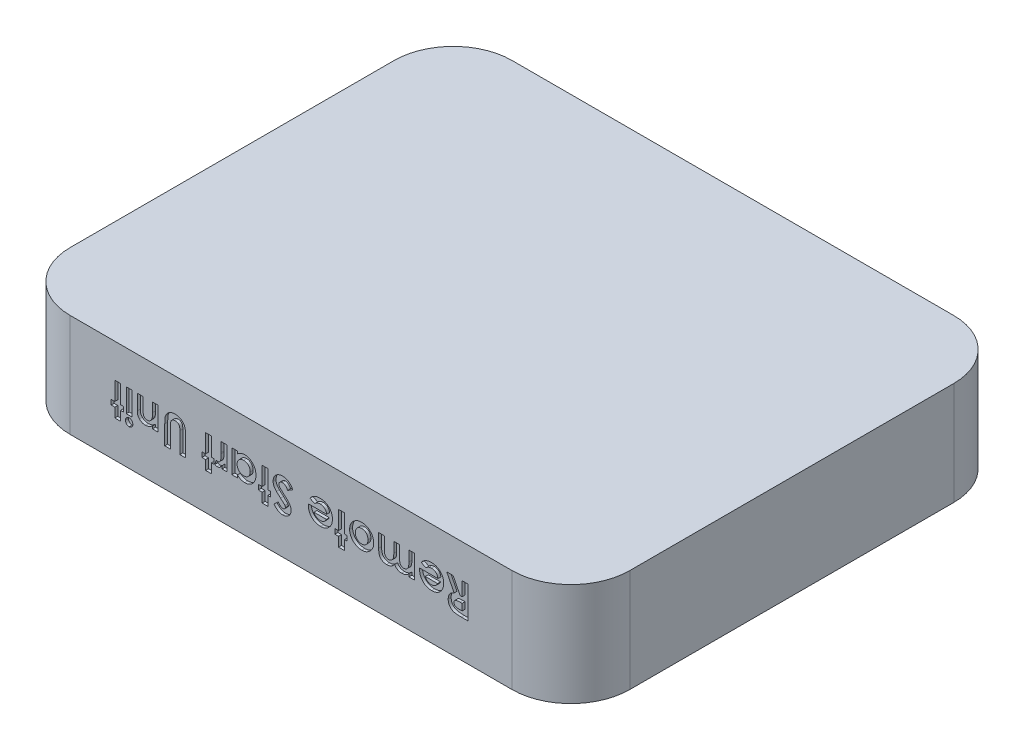
SolidWorks part; units mm, degrees
ref_plane "Front Plane" through (0, 0, 0) normal (0, 0, 1) x (1, 0, 0)
ref_plane "Top Plane" through (0, 0, 0) normal (0, 1, 0) x (1, 0, 0)
ref_plane "Right Plane" through (0, 0, 0) normal (1, 0, 0) x (0, 0, -1)
sketch "Sketch1" plane through (0, 0, 0) normal (0, 1, 0) x (1, 0, 0)
  line L0 (-60.325, -47.625) -> (60.325, -47.625)
  line L1 (-57.15, -44.45) -> (57.15, -44.45)
  line L2 (-57.15, -44.45) -> (-57.15, 44.45)
  line L3 (-57.15, 44.45) -> (57.15, 44.45)
  line L4 (57.15, -44.45) -> (57.15, 44.45)
  line L5 (-57.15, -44.45) -> (57.15, 44.45) construction
  line L6 (-57.15, 44.45) -> (57.15, -44.45) construction
  line L7 (60.325, -47.625) -> (60.325, 47.625)
  line L8 (-60.325, 47.625) -> (60.325, 47.625)
  line L9 (-60.325, -47.625) -> (-60.325, 47.625)
  point P0 (0, 0)
  dimension "D1" = 114.3
  dimension "D2" = 88.9
  dimension "D3" = 3.175
extrude "Boss-Extrude1" add sketch "Sketch1" along normal blind 19.05
fillet "Fillet1" radius 12.7 8 edges at (57.15, 9.525, 44.45) (57.15, 9.525, -44.45) (-57.15, 9.525, -44.45) (-57.15, 9.525, 44.45) (60.325, 9.525, -47.625) (60.325, 9.525, 47.625) (-60.325, 9.525, -47.625) (-60.325, 9.525, 47.625)
sketch "Sketch2" plane through (0, 19.05, 0) normal (0, 1, 0) x (1, 0, 0)
  line L4 (60.325, -34.925) -> (60.325, 34.925)
  line L5 (47.625, 47.625) -> (-47.625, 47.625)
  line L6 (-60.325, 34.925) -> (-60.325, -34.925)
  line L7 (-47.625, -47.625) -> (47.625, -47.625)
  line L8 (60.325, -34.925) -> (60.325, 34.925)
  line L9 (47.625, 47.625) -> (-47.625, 47.625)
  line L10 (-60.325, 34.925) -> (-60.325, -34.925)
  line L11 (-47.625, -47.625) -> (47.625, -47.625)
  arc A4 (60.325, 34.925) -> (47.625, 47.625) centre (47.625, 34.925) ccw
  arc A5 (-47.625, 47.625) -> (-60.325, 34.925) centre (-47.625, 34.925) ccw
  arc A6 (-60.325, -34.925) -> (-47.625, -47.625) centre (-47.625, -34.925) ccw
  arc A7 (47.625, -47.625) -> (60.325, -34.925) centre (47.625, -34.925) ccw
  arc A8 (60.325, 34.925) -> (47.625, 47.625) centre (47.625, 34.925) ccw
  arc A9 (-47.625, 47.625) -> (-60.325, 34.925) centre (-47.625, 34.925) ccw
  arc A10 (-60.325, -34.925) -> (-47.625, -47.625) centre (-47.625, -34.925) ccw
  arc A11 (47.625, -47.625) -> (60.325, -34.925) centre (47.625, -34.925) ccw
  dimension "D1" = 0
extrude "Boss-Extrude2" add sketch "Sketch2" along normal blind 3.175 contours A10 L11 A11 L8 A8 L9 A9 L10
sketch "Sketch3" plane through (0, 0, -44.45) normal (0, 0, 1) x (1, 0, 0)
  line L0 (0, -16.51) -> (0, 16.51) construction
  line L1 (44.45, 0) -> (-44.45, 0) construction
  line L2 (-2.54, -16.51) -> (-2.54, 16.51)
  line L3 (2.54, -16.51) -> (2.54, 16.51)
  line L4 (44.45, 19.05) -> (-44.45, 19.05) construction
  arc A0 (-2.54, -16.51) -> (2.54, -16.51) centre (0, -16.51) ccw
  arc A1 (2.54, 16.51) -> (-2.54, 16.51) centre (0, 16.51) ccw
  point P4 (0, 0)
  point P9 (0, 19.05)
  dimension "D1" = 5.08
extrude "Cut-Extrude1" cut sketch "Sketch3" against normal through all
fillet "Fillet2" radius 6.35 2 edges at (-2.54, 0, -46.0375) (2.54, 0, -46.0375)
fillet "Fillet3" [suppressed] radius 6.35
sketch "Sketch4" plane through (0, 0, 47.625) normal (0, 0, 1) x (1, 0, 0)
  line L0 (-47.625, 14.9465) -> (47.625, 14.9465) construction
  line L1 (-47.625, 22.225) -> (-47.625, 0) construction
  line L2 (47.625, 0) -> (47.625, 22.225) construction
  text T0 "<b>Remote Start Unit</b>" font "Century Gothic" height in points 26
extrude "Cut-Extrude2" cut sketch "Sketch4" against normal blind 0.635
